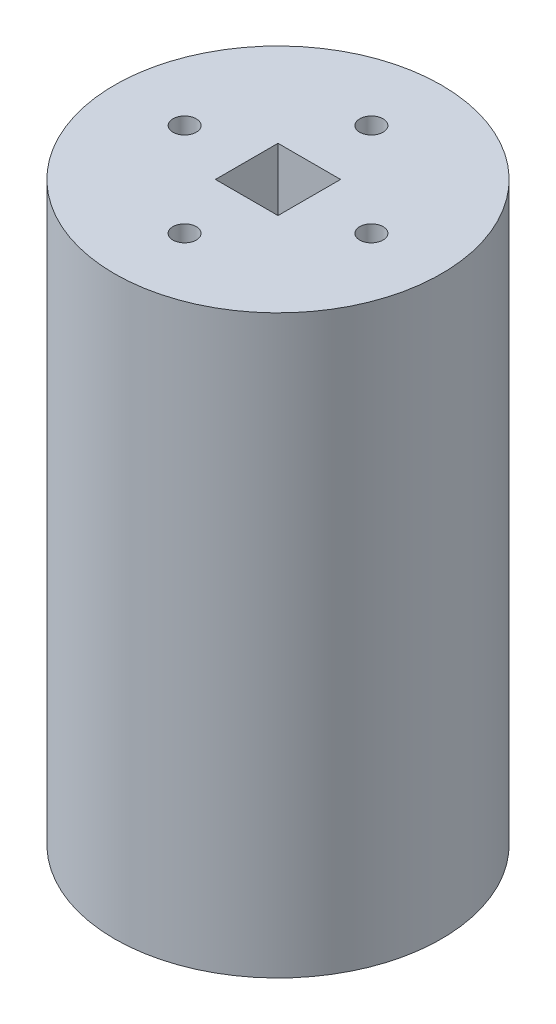
SolidWorks part; units mm, degrees
material "ABS"
ref_plane "Front Plane" through (0, 0, 0) normal (0, 0, 1) x (1, 0, 0)
ref_plane "Top Plane" through (0, 0, 0) normal (0, 1, 0) x (1, 0, 0)
ref_plane "Right Plane" through (0, 0, 0) normal (1, 0, 0) x (0, 0, -1)
sketch "Sketch1" plane through (0, 0, 0) normal (0, 1, 0) x (1, 0, 0)
  line L1 (-3.35, 3.35) -> (3.35, 3.35)
  line L2 (-3.35, 3.35) -> (-3.35, -3.35)
  line L3 (-3.35, -3.35) -> (3.35, -3.35)
  line L4 (3.35, 3.35) -> (3.35, -3.35)
  circle A0 centre (0, 0) radius 17.5
  circle A1 centre (0, 0) radius 10 construction
  circle A2 centre (0, 10) radius 1.5 construction
  circle A3 centre (10, 0) radius 1.5 construction
  circle A4 centre (0, -10) radius 1.5 construction
  circle A5 centre (-10, 0) radius 1.5 construction
  arc A6 (17.5, 0) -> (0, -17.5) centre (35.6468, -35.6468) ccw
  point P8 (0, 3.35)
  point P9 (-3.35, 0)
  point P21 (0, 0)
  dimension "D1" = 20
  dimension "D2" = 35
  dimension "D4" = 3
  dimension "D6" = 40
  dimension "D3" = 6.7
  dimension "D5" = 4
extrude "Boss-Extrude1" add sketch "Sketch1" against normal blind 61.675 contours A0 A6 | A6 A0 L1 L4 L3 L2
hole_wizard "Tap Drill for M3x0.5 Tap1" positions "3DSketch1" profile "Sketch2" hole size "M3x0.5" standard "ANSI Metric" end condition up to next
sketch3d "3DSketch1"
  point P18 (0, 0, -10)
  point P20 (10, 0, 0)
  point P22 (-10, 0, 0)
  point P24 (0, 0, 10)
sketch "Sketch2" plane through (0, 0, -10) normal (1, 0, 0) x (0, 0, 1)
  line L0 (0, 0) -> (0, 61.675)
  line L1 (0, 61.675) -> (1.25, 61.675)
  line L2 (1.25, 61.675) -> (1.25, 0)
  line L5 (1.25, 0) -> (0, 0)
  line L11 (0, -6.35) -> (0, 107.95) construction
  dimension "Thru Hole Dia." = 2.5
  dimension "Thru Hole Depth" = 61.675
fillet "Fillet1" [suppressed] radius 2
